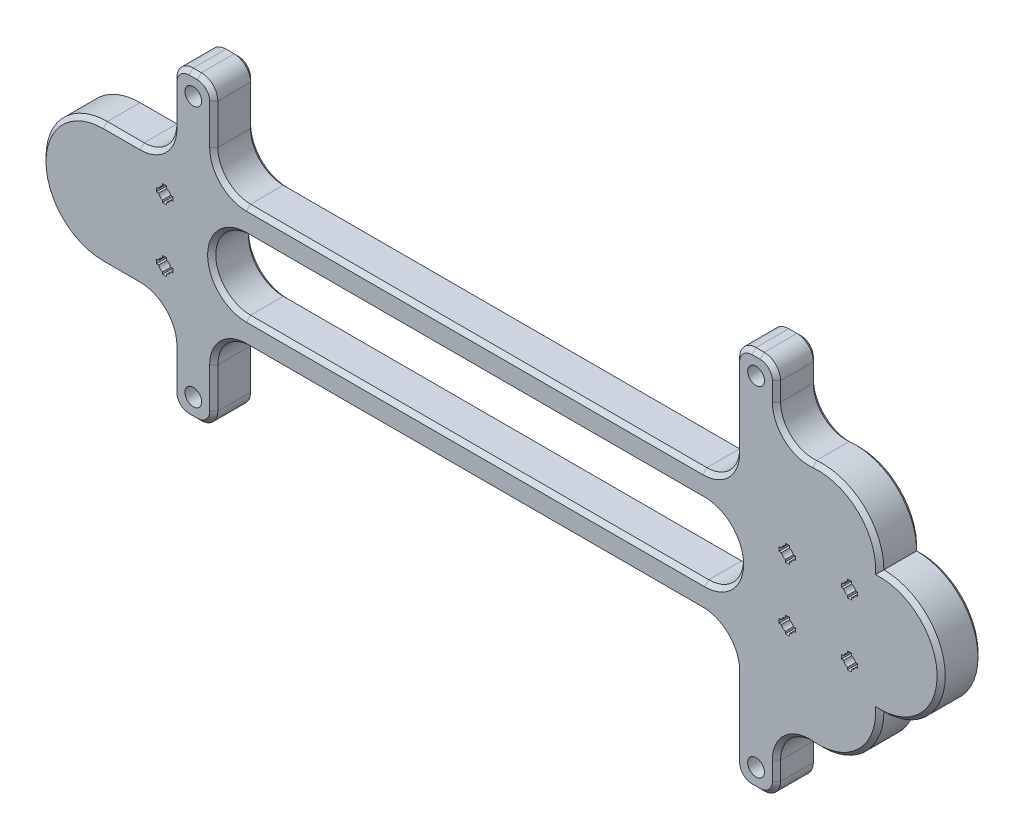
SolidWorks part; units mm, degrees
ref_plane "Front Plane" through (0, 0, 0) normal (0, 0, 1) x (1, 0, 0)
ref_plane "Top Plane" through (0, 0, 0) normal (0, 1, 0) x (1, 0, 0)
ref_plane "Right Plane" through (0, 0, 0) normal (1, 0, 0) x (0, 0, -1)
sketch "Sketch1" plane through (0, 0, 0) normal (0, 0, 1) x (1, 0, 0)
  line L0 (15, 7.4) -> (144.8, 7.4)
  line L5 (4.248, -53.425) -> (147.848, -53.425) construction
  line L6 (4.248, -53.425) -> (4.248, 38.225) construction
  line L7 (178.123, -7.6) -> (216.3549, -7.6) construction
  line L8 (159.8, 9.5794) -> (159.8, -13.3936) construction
  line L9 (166.9, -2) -> (167.9, -2)
  line L10 (166.9, -2) -> (166.9, -1.4671)
  line L11 (166.9, 2) -> (167.9, 2)
  line L12 (167.9, -2) -> (167.9, -1.4671)
  line L13 (166.9, -2) -> (167.9, 2) construction
  line L14 (166.9, 2) -> (167.9, -2) construction
  line L15 (165.4, -0.5) -> (165.9329, -0.5)
  line L16 (165.4, -0.5) -> (165.4, 0.5)
  line L17 (165.4, 0.5) -> (165.9329, 0.5)
  line L18 (169.4, -0.5) -> (169.4, 0.5)
  line L19 (165.4, -0.5) -> (169.4, 0.5) construction
  line L20 (165.4, 0.5) -> (169.4, -0.5) construction
  line L21 (167.9, 1.4671) -> (167.9, 2)
  line L22 (168.8671, 0.5) -> (169.4, 0.5)
  line L23 (166.9, 1.4671) -> (166.9, 2)
  line L24 (168.8671, -0.5) -> (169.4, -0.5)
  line L25 (154.2, -0.5) -> (154.2, 0.5)
  line L26 (154.2, 0.5) -> (153.6671, 0.5)
  line L27 (152.7, 1.4671) -> (152.7, 2)
  line L28 (152.7, 2) -> (151.7, 2)
  line L29 (151.7, 1.4671) -> (151.7, 2)
  line L30 (150.7329, 0.5) -> (150.2, 0.5)
  line L31 (150.2, -0.5) -> (150.2, 0.5)
  line L32 (150.7329, -0.5) -> (150.2, -0.5)
  line L33 (151.7, -2) -> (151.7, -1.4671)
  line L34 (152.7, -2) -> (151.7, -2)
  line L35 (152.7, -2) -> (152.7, -1.4671)
  line L36 (154.2, -0.5) -> (153.6671, -0.5)
  line L37 (154.2, -14.7) -> (153.6671, -14.7)
  line L38 (152.7, -13.2) -> (152.7, -13.7329)
  line L39 (152.7, -13.2) -> (151.7, -13.2)
  line L40 (151.7, -13.2) -> (151.7, -13.7329)
  line L41 (150.7329, -14.7) -> (150.2, -14.7)
  line L42 (150.2, -14.7) -> (150.2, -15.7)
  line L43 (150.7329, -15.7) -> (150.2, -15.7)
  line L44 (151.7, -16.6671) -> (151.7, -17.2)
  line L45 (152.7, -17.2) -> (151.7, -17.2)
  line L46 (152.7, -16.6671) -> (152.7, -17.2)
  line L47 (154.2, -15.7) -> (153.6671, -15.7)
  line L48 (154.2, -14.7) -> (154.2, -15.7)
  line L49 (165.4, -14.7) -> (165.4, -15.7)
  line L50 (165.4, -15.7) -> (165.9329, -15.7)
  line L51 (166.9, -16.6671) -> (166.9, -17.2)
  line L52 (166.9, -17.2) -> (167.9, -17.2)
  line L53 (167.9, -16.6671) -> (167.9, -17.2)
  line L54 (168.8671, -15.7) -> (169.4, -15.7)
  line L55 (169.4, -14.7) -> (169.4, -15.7)
  line L56 (168.8671, -14.7) -> (169.4, -14.7)
  line L57 (167.9, -13.2) -> (167.9, -13.7329)
  line L58 (166.9, -13.2) -> (167.9, -13.2)
  line L59 (166.9, -13.2) -> (166.9, -13.7329)
  line L60 (165.4, -14.7) -> (165.9329, -14.7)
  line L61 (144.8, -22.6) -> (174.8, -22.6)
  line L62 (144.8, -22.6) -> (144.8, 7.4)
  line L63 (144.8, 7.4) -> (174.8, 7.4)
  line L64 (174.8, -22.6) -> (174.8, 7.4)
  line L65 (144.8, -22.6) -> (174.8, 7.4) construction
  line L66 (144.8, 7.4) -> (174.8, -22.6) construction
  line L67 (-0.5, -2) -> (0.5, -2)
  line L68 (-0.5, -2) -> (-0.5, -1.4671)
  line L69 (-0.5, 2) -> (0.5, 2)
  line L70 (0.5, -2) -> (0.5, -1.4671)
  line L71 (-2, -0.5) -> (-1.4671, -0.5)
  line L72 (-2, -0.5) -> (-2, 0.5)
  line L73 (-2, 0.5) -> (-1.4671, 0.5)
  line L74 (1.998, -0.5) -> (1.998, 0.5)
  line L75 (0.5, 1.4671) -> (0.5, 2)
  line L76 (1.4671, 0.5) -> (1.998, 0.5)
  line L77 (-0.5, 1.4671) -> (-0.5, 2)
  line L78 (1.4671, -0.5) -> (1.998, -0.5)
  line L79 (1.998, -14.7) -> (1.998, -15.7)
  line L80 (1.998, -15.7) -> (1.4671, -15.7)
  line L81 (-0.5, -16.6671) -> (-0.5, -17.2)
  line L82 (-0.5, -17.2) -> (0.5, -17.2)
  line L83 (0.5, -16.6671) -> (0.5, -17.2)
  line L84 (-1.4671, -15.7) -> (-2, -15.7)
  line L85 (-2, -14.7) -> (-2, -15.7)
  line L87 (0.5, -13.2) -> (0.5, -13.7329)
  line L88 (-0.5, -13.2) -> (0.5, -13.2)
  line L89 (-0.5, -13.2) -> (-0.5, -13.7329)
  line L90 (1.998, -14.7) -> (1.4671, -14.7)
  line L91 (0, 0) -> (0, -15.2) construction
  line L92 (4.248, 38.225) -> (147.848, 38.225) construction
  line L93 (-15, -22.6) -> (15, -22.6)
  line L94 (-15, -22.6) -> (-15, 7.4)
  line L95 (-15, 7.4) -> (15, 7.4)
  line L96 (15, -22.6) -> (15, 7.4)
  line L97 (-15, -22.6) -> (15, 7.4) construction
  line L98 (-15, 7.4) -> (15, -22.6) construction
  line L99 (147.848, -53.425) -> (147.848, 38.225) construction
  line L100 (4.248, -53.425) -> (147.848, 38.225) construction
  line L101 (4.248, 38.225) -> (147.848, -53.425) construction
  line L102 (15, -22.6) -> (144.8, -22.6)
  line L103 (1.998, 7.4) -> (1.998, 29.225)
  line L104 (1.998, 29.225) -> (11.998, 29.225)
  line L105 (11.998, 29.225) -> (11.998, 7.4)
  line L106 (1.998, -22.6) -> (1.998, -44.425)
  line L107 (1.998, -44.425) -> (11.998, -44.425)
  line L108 (11.998, -44.425) -> (11.998, -22.6)
  line L109 (139.548, -22.6) -> (139.548, -54.025)
  line L110 (139.548, -54.025) -> (149.548, -54.025)
  line L111 (149.548, -54.025) -> (149.548, -33.5497)
  line L112 (139.548, 7.4) -> (139.548, 38.825)
  line L113 (139.548, 38.825) -> (149.548, 38.825)
  line L114 (149.548, 38.825) -> (149.548, 18.3497)
  line L115 (-1.4671, -14.7) -> (-2, -14.7)
  arc A2 (166.9, 1.4671) -> (165.9329, 0.5) centre (167.4, 0) ccw
  arc A3 (165.9329, -0.5) -> (166.9, -1.4671) centre (167.4, 0) ccw
  arc A4 (168.8671, 0.5) -> (167.9, 1.4671) centre (167.4, 0) ccw
  arc A5 (167.9, -1.4671) -> (168.8671, -0.5) centre (167.4, 0) ccw
  arc A6 (152.7, 1.4671) -> (153.6671, 0.5) centre (152.2, 0) cw
  arc A7 (150.7329, 0.5) -> (151.7, 1.4671) centre (152.2, 0) cw
  arc A8 (151.7, -1.4671) -> (150.7329, -0.5) centre (152.2, 0) cw
  arc A9 (153.6671, -0.5) -> (152.7, -1.4671) centre (152.2, 0) cw
  arc A10 (153.6671, -14.7) -> (152.7, -13.7329) centre (152.2, -15.2) ccw
  arc A11 (151.7, -13.7329) -> (150.7329, -14.7) centre (152.2, -15.2) ccw
  arc A12 (150.7329, -15.7) -> (151.7, -16.6671) centre (152.2, -15.2) ccw
  arc A13 (152.7, -16.6671) -> (153.6671, -15.7) centre (152.2, -15.2) ccw
  arc A14 (166.9, -16.6671) -> (165.9329, -15.7) centre (167.4, -15.2) cw
  arc A15 (168.8671, -15.7) -> (167.9, -16.6671) centre (167.4, -15.2) cw
  arc A16 (167.9, -13.7329) -> (168.8671, -14.7) centre (167.4, -15.2) cw
  arc A17 (165.9329, -14.7) -> (166.9, -13.7329) centre (167.4, -15.2) cw
  arc A18 (144.8, 7.4) -> (174.8, 7.4) centre (159.8, 7.4) cw
  arc A19 (174.8, 7.4) -> (174.8, -22.6) centre (174.8, -7.6) cw
  arc A20 (174.8, -22.6) -> (144.8, -22.6) centre (159.8, -22.6) cw
  arc A21 (-0.5, 1.4671) -> (-1.4671, 0.5) centre (0, 0) ccw
  arc A22 (-1.4671, -0.5) -> (-0.5, -1.4671) centre (0, 0) ccw
  arc A23 (1.4671, 0.5) -> (0.5, 1.4671) centre (0, 0) ccw
  arc A24 (0.5, -1.4671) -> (1.4671, -0.5) centre (0, 0) ccw
  arc A25 (-0.5, -16.6671) -> (-1.4671, -15.7) centre (0, -15.2) cw
  arc A26 (1.4671, -15.7) -> (0.5, -16.6671) centre (0, -15.2) cw
  arc A27 (0.5, -13.7329) -> (1.4671, -14.7) centre (0, -15.2) cw
  arc A28 (-1.4671, -14.7) -> (-0.5, -13.7329) centre (0, -15.2) cw
  arc A29 (-15, 7.4) -> (-15, -22.6) centre (-15, -7.6) ccw
  circle A30 centre (6.998, 24.225) radius 2.05
  circle A31 centre (6.998, -39.425) radius 2.05
  circle A32 centre (144.548, -49.025) radius 2.05
  circle A33 centre (144.548, 33.825) radius 2.05
  point P0 (76.048, -7.6)
  point P83 (159.8, -7.6)
  point P128 (0, -7.6)
  dimension "D4" = 4.1
  dimension "D2" = 91.65
  dimension "D3" = 143.6
  dimension "D5" = 30
  dimension "D6" = 30
  dimension "D7" = 152.2
  dimension "D8" = 2.75
  dimension "D9" = 7.6
  dimension "D10" = 15.2
  dimension "D11" = 14
  dimension "D12" = 14
  dimension "D13" = 2.75
  dimension "D14" = 4.4
  dimension "D15" = 3.3
  dimension "D16" = 3.3
  dimension "D17" = 4.4
  dimension "D18" = 5
  dimension "D19" = 5
  dimension "D20" = 5
  dimension "D21" = 5
  dimension "D22" = 5
  dimension "D23" = 5
  dimension "D24" = 5
  dimension "D25" = 5
  dimension "D26" = 5
  dimension "D27" = 5
  dimension "D28" = 5
  dimension "D29" = 5
extrude "Boss-Extrude1" add sketch "Sketch1" along normal blind 10
fillet "Fillet2" radius 8 8 edges at (149.548, -33.5497, 5) (149.548, 18.3497, 5) (139.548, 7.4, 5) (139.548, -22.6, 5) (1.998, -22.6, 5) (11.998, -22.6, 5) (1.998, 7.4, 5) (11.998, 7.4, 5)
fillet "Fillet3" radius 4 8 edges at (1.998, 29.225, 5) (11.998, 29.225, 5) (1.998, -44.425, 5) (11.998, -44.425, 5) (139.548, -54.025, 5) (149.548, -54.025, 5) (139.548, 38.825, 5) (149.548, 38.825, 5)
chamfer "Chamfer1" distance 1 angle 45 36 edges at (-30, -7.6, 0) (169.874, 18.5137, 0) (189.8, -7.6, 0) (169.874, -33.7137, 0) (149.548, 32.5572, 0) (149.548, -47.7572, 0) (152.1752, 24.3622, 0) (152.1752, -39.5622, 0) (-10.501, 7.4, 0) (-10.501, -22.6, 0) (-0.3452, 9.7431, 0) (-0.3452, -24.9431, 0) (1.998, 20.3125, 0) (1.998, -35.5125, 0) (3.1696, 28.0534, 0) (3.1696, -43.2534, 0) (6.998, 29.225, 0) (6.998, -44.425, 0) (10.8264, 28.0534, 0) (10.8264, -43.2534, 0) (11.998, 20.3125, 0) (11.998, -35.5125, 0) (14.3411, 9.7431, 0) (14.3411, -24.9431, 0) (75.773, 7.4, 0) (75.773, -22.6, 0) (137.2048, 9.7431, 0) (137.2048, -24.9431, 0) (139.548, 25.1125, 0) (139.548, -40.3125, 0) (140.7196, 37.6534, 0) (140.7196, -52.8534, 0) (144.548, 38.825, 0) (144.548, -54.025, 0) (148.3764, 37.6534, 0) (148.3764, -52.8534, 0)
chamfer "Chamfer2" distance 1 angle 45 36 edges at (169.874, 18.5137, 10) (152.1752, 24.3622, 10) (149.548, 32.5572, 10) (148.3764, 37.6534, 10) (144.548, 38.825, 10) (140.7196, 37.6534, 10) (139.548, 25.1125, 10) (137.2048, 9.7431, 10) (75.773, 7.4, 10) (14.3411, 9.7431, 10) (11.998, 20.3125, 10) (10.8264, 28.0534, 10) (6.998, 29.225, 10) (3.1696, 28.0534, 10) (1.998, 20.3125, 10) (-0.3452, 9.7431, 10) (-10.501, 7.4, 10) (-30, -7.6, 10) (-10.501, -22.6, 10) (169.874, -33.7137, 10) (-0.3452, -24.9431, 10) (152.1752, -39.5622, 10) (1.998, -35.5125, 10) (149.548, -47.7572, 10) (3.1696, -43.2534, 10) (148.3764, -52.8534, 10) (6.998, -44.425, 10) (144.548, -54.025, 10) (10.8264, -43.2534, 10) (140.7196, -52.8534, 10) (11.998, -35.5125, 10) (139.548, -40.3125, 10) (14.3411, -24.9431, 10) (137.2048, -24.9431, 10) (75.773, -22.6, 10) (189.8, -7.6, 10)
sketch "Sketch2" plane through (0, 0, 10) normal (0, 0, 1) x (1, 0, 0)
  line L0 (19.998, -7.6) -> (131.998, -7.6) construction
  line L1 (19.998, 0.9) -> (131.998, 0.9)
  line L2 (19.998, -16.1) -> (131.998, -16.1)
  line L3 (75.998, 6.4) -> (75.998, -21.6) construction
  line L4 (131.548, 6.4) -> (19.998, 6.4) construction
  line L5 (19.998, -21.6) -> (131.548, -21.6) construction
  arc A0 (19.998, 0.9) -> (19.998, -16.1) centre (19.998, -7.6) ccw
  arc A1 (131.998, -16.1) -> (131.998, 0.9) centre (131.998, -7.6) ccw
  point P2 (75.998, -7.6)
  point P13 (75.998, -7.6)
  dimension "D1" = 112
  dimension "D2" = 17
extrude "Cut-Extrude1" cut sketch "Sketch2" against normal through all
chamfer "Chamfer3" distance 1 angle 45 8 edges at (75.998, 0.9, 10) (75.998, 0.9, 0) (11.498, -7.6, 10) (11.498, -7.6, 0) (140.498, -7.6, 10) (140.498, -7.6, 0) (75.998, -16.1, 10) (75.998, -16.1, 0)
